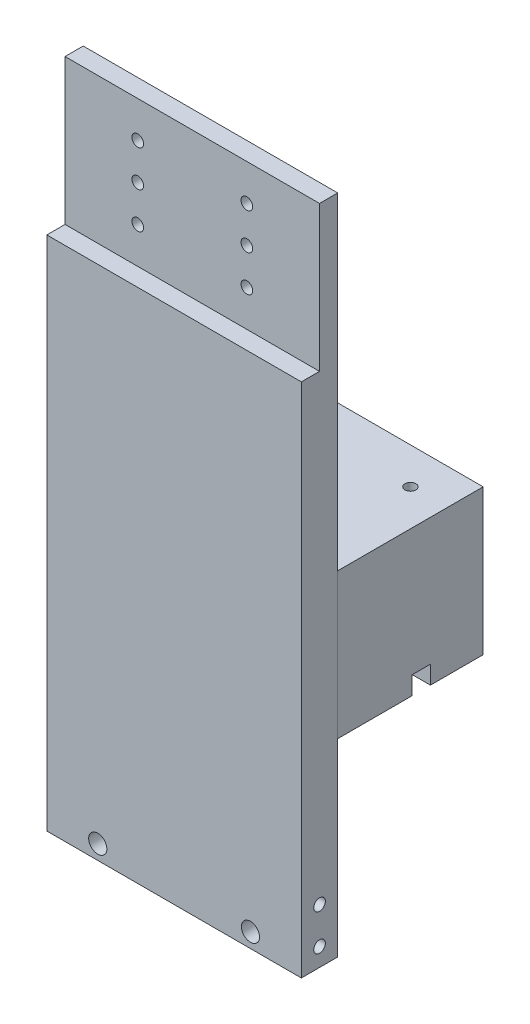
SolidWorks part; units mm, degrees
ref_plane "前视基准面" through (0, 0, 0) normal (0, 0, 1) x (1, 0, 0)
ref_plane "上视基准面" through (0, 0, 0) normal (0, 1, 0) x (1, 0, 0)
ref_plane "右视基准面" through (0, 0, 0) normal (1, 0, 0) x (0, 0, -1)
other "Configuration Table"
sketch "草图1" plane through (0, 0, 0) normal (0, 1, 0) x (1, 0, 0)
  line L1 (-32.1359, 17.2849) -> (37.8641, 17.2849)
  line L2 (-32.1359, 17.2849) -> (-32.1359, -22.7151)
  line L3 (-32.1359, -22.7151) -> (37.8641, -22.7151)
  line L4 (37.8641, 17.2849) -> (37.8641, -22.7151)
  dimension "D1" = 70
  dimension "D2" = 40
extrude "凸台-拉伸1" add sketch "草图1" along normal blind 40
sketch "草图2" plane through (0, 0, 0) normal (0, -1, 0) x (1, 0, 0)
  line L0 (-33.606, 17.7151) -> (40.5423, 17.7151) construction
  line L1 (-32.1359, 22.7151) -> (37.8641, 22.7151) construction
  line L2 (2.8641, 22.7151) -> (2.8641, -17.2849) construction
  line L3 (37.8641, -17.2849) -> (-32.1359, -17.2849) construction
  line L5 (-41.0082, -7.2849) -> (62.2571, -7.2849) construction
  circle A0 centre (-22.1359, 17.7151) radius 1.5
  circle A1 centre (27.8641, 17.7151) radius 1.5
  circle A2 centre (-22.1359, -7.2849) radius 1.5
  circle A3 centre (27.8641, -7.2849) radius 1.5
  dimension "D2" = 25
  dimension "D4" = 25
  dimension "D1" = 5
  dimension "D3" = 10
extrude "切除-拉伸1" cut sketch "草图2" against normal through all
sketch "草图4" plane through (0, 0, 0) normal (0, -1, 0) x (1, 0, 0)
  line L0 (-32.1359, 22.7151) -> (-32.1359, 32.7151)
  line L1 (-32.1359, 32.7151) -> (37.8641, 32.7151)
  line L2 (37.8641, 32.7151) -> (37.8641, 22.7151)
  line L3 (37.8641, 22.7151) -> (-32.1359, 22.7151)
  dimension "D1" = 10
extrude "凸台-拉伸2" add sketch "草图4" along normal blind 52 and the other way blind 236 separate body contours L3 L0 L1 L2
sketch "草图5" plane through (0, 0, 32.7151) normal (0, 0, 1) x (1, 0, 0)
  line L0 (-38.373, -48) -> (39.7493, -48) construction
  line L1 (-32.1359, -52) -> (37.8641, -52) construction
  line L2 (2.8641, 0) -> (2.8641, -52) construction
  line L3 (-32.1359, 0) -> (37.8641, 0) construction
  circle A0 centre (-18.1359, -48) radius 2.5
  circle A1 centre (23.8641, -48) radius 2.5
  dimension "D2" = 21
  dimension "D1" = 4
extrude "切除-拉伸2" cut sketch "草图5" against normal blind 10
sketch "草图6" plane through (0, 0, 32.7151) normal (0, 0, 1) x (1, 0, 0)
  line L0 (-39.8379, 212) -> (51.2489, 212) construction
  line L1 (-32.1359, 236) -> (37.8641, 236) construction
  line L2 (2.8641, 236) -> (2.8641, 203.179) construction
  circle A0 centre (-18.1359, 212) radius 3
  circle A1 centre (23.8641, 212) radius 3
  dimension "D2" = 21
  dimension "D1" = 24
extrude "切除-拉伸3" cut sketch "草图6" against normal blind 10
sketch "草图7" plane through (0, 0, 22.7151) normal (0, 0, -1) x (-1, 0, 0)
  line L0 (-37.8641, 236) -> (-37.8641, 246)
  line L1 (-37.8641, 246) -> (32.1359, 246)
  line L2 (32.1359, 246) -> (32.1359, 236)
  line L3 (32.1359, 236) -> (-37.8641, 236)
  dimension "D1" = 10
extrude "凸台-拉伸3" add sketch "草图7" against normal blind 50
sketch "草图8" plane through (0, 236, 0) normal (0, -1, 0) x (1, 0, 0)
  line L0 (-32.1359, 72.7151) -> (37.8641, 32.7151) construction
  line L1 (37.8641, 72.7151) -> (-32.1359, 32.7151) construction
  circle A0 centre (2.8641, 52.7151) radius 12.5
extrude "切除-拉伸4" cut sketch "草图8" against normal blind 10
sketch "草图12" plane through (0, 246, 0) normal (0, 1, 0) x (1, 0, 0)
  line L0 (2.8641, -52.7151) -> (49.57, -52.7151) construction
  line L1 (2.8641, -52.7151) -> (-42.4096, -52.7151) construction
  line L2 (2.8641, -22.7151) -> (2.8641, -78.6614) construction
  line L3 (-32.1359, -22.7151) -> (37.8641, -22.7151) construction
  line L4 (-14.6359, -35.2151) -> (-14.6359, -70.2151) construction
  line L5 (-16.6359, -33.2151) -> (22.3641, -33.2151)
  line L6 (-16.6359, -33.2151) -> (-16.6359, -72.2151)
  line L7 (-16.6359, -72.2151) -> (22.3641, -72.2151)
  line L8 (22.3641, -33.2151) -> (22.3641, -72.2151)
  line L9 (-14.6359, -70.2151) -> (20.3641, -70.2151) construction
  line L10 (20.3641, -35.2151) -> (20.3641, -70.2151) construction
  line L11 (-14.6359, -35.2151) -> (20.3641, -35.2151) construction
  dimension "D1" = 39
  dimension "D2" = 39
  dimension "D3" = 19.5
  dimension "D5" = 19.5
  dimension "D4" = 2
extrude "拉伸-薄壁2" add sketch "草图12" along normal blind 15 thin
sketch "草图14" plane through (0, 261, 0) normal (0, 1, 0) x (1, 0, 0)
  line L0 (-16.6359, -52.7151) -> (22.3641, -52.7151) construction
  line L1 (-16.6359, -33.2151) -> (-16.6359, -72.2151) construction
  line L2 (22.3641, -72.2151) -> (22.3641, -33.2151) construction
  line L3 (2.8641, -33.2151) -> (2.8641, -72.2151) construction
  line L4 (22.3641, -33.2151) -> (-16.6359, -33.2151) construction
  line L5 (-16.6359, -72.2151) -> (22.3641, -72.2151) construction
  circle A0 centre (-12.6359, -37.2151) radius 2
  circle A1 centre (18.3641, -37.2151) radius 2
  circle A2 centre (-12.6359, -68.2151) radius 2
  circle A3 centre (18.3641, -68.2151) radius 2
  dimension "D1" = 15.5
  dimension "D2" = 15.5
extrude "切除-拉伸5" cut sketch "草图14" against normal blind 25
sketch "草图15" plane through (0, 0, 0) normal (0, -1, 0) x (1, 0, 0)
  line L0 (-32.1359, -0.2849) -> (37.8641, -0.2849) construction
  line L1 (-32.1359, -17.2849) -> (-32.1359, 22.7151) construction
  line L2 (37.8641, 22.7151) -> (37.8641, -17.2849) construction
  line L3 (-32.1359, 2.2151) -> (37.8641, 2.2151)
  line L4 (37.8641, 2.2151) -> (37.8641, -2.7849)
  line L5 (37.8641, -2.7849) -> (-32.1359, -2.7849)
  line L6 (-32.1359, -2.7849) -> (-32.1359, 2.2151)
  circle A0 centre (-22.1359, -7.2849) radius 1.5 construction
  dimension "D1" = 7
  dimension "D2" = 5
  dimension "D3" = 2.5
extrude "切除-拉伸6" cut sketch "草图15" against normal blind 5
sketch "草图16" plane through (-32.1359, 0, 0) normal (-1, 0, 0) x (0, 0, 1)
  line L0 (22.7151, 246) -> (72.7151, 246)
  line L1 (72.7151, 246) -> (72.7151, 236)
  line L2 (72.7151, 236) -> (22.7151, 236)
  line L3 (22.7151, 246) -> (22.7151, -52) construction
  line L4 (22.7151, 236) -> (22.7151, 246)
extrude "凸台-拉伸5" add sketch "草图16" along normal blind 10
ref_plane "基准面3" through (0, 97, 0) normal (0, 1, 0) x (1, 0, 0)
mirror "镜向1" about plane through (0, 97, 0) normal (0, 1, 0) of "凸台-拉伸5"
ref_plane "基准面4" through (2.8641, 0, 0) normal (-1, 0, 0) x (0, 0, 1)
mirror "镜向2" about plane through (2.8641, 0, 0) normal (-1, 0, 0) of "镜向1", "凸台-拉伸5"
sketch "草图17" plane through (0, -52, 0) normal (0, -1, 0) x (1, 0, 0)
  line L0 (-32.1359, 52.7151) -> (37.8641, 52.7151) construction
  line L1 (-32.1359, 72.7151) -> (-32.1359, 32.7151) construction
  line L2 (37.8641, 72.7151) -> (37.8641, 32.7151) construction
  line L3 (2.8641, 72.7151) -> (2.8641, 32.7151) construction
  line L4 (47.8641, 72.7151) -> (-42.1359, 72.7151) construction
  line L5 (-32.1359, 32.7151) -> (37.8641, 32.7151) construction
  circle A0 centre (-37.1359, 52.7151) radius 2.5
  circle A1 centre (42.8641, 52.7151) radius 2.5
  dimension "D1" = 5
extrude "切除-拉伸7" cut sketch "草图17" against normal through all
sketch "草图18" plane through (0, -52, 0) normal (0, -1, 0) x (1, 0, 0)
  circle A0 centre (-37.1359, 52.7151) radius 2.5
  circle A1 centre (42.8641, 52.7151) radius 2.5
extrude "凸台-拉伸6" add sketch "草图18" against normal blind 5
sketch "草图21" plane through (0, 0, 22.7151) normal (0, 0, -1) x (-1, 0, 0)
  line L1 (-37.8641, 236) -> (-37.8641, -42) construction
  line L2 (-37.8641, -32) -> (-37.8641, -42)
  line L3 (-37.8641, -42) -> (-47.8641, -42)
  line L4 (-37.8641, -32) -> (-47.8641, -32)
  line L5 (-47.8641, -32) -> (-47.8641, -42)
  dimension "D1" = 10
extrude "凸台-拉伸8" add sketch "草图21" against normal up to surface (10 mm away) up to face at (-15.1359, 212, 32.7151)
mirror "镜向3" about plane through (2.8641, 0, 0) normal (-1, 0, 0) of "凸台-拉伸8"
sketch "草图22" plane through (47.8641, 0, 0) normal (1, 0, 0) x (0, 0, -1)
  line L0 (-32.7151, -32) -> (-42.7151, -42)
  line L1 (-32.7151, -42) -> (-72.7151, -42) construction
  line L2 (-42.7151, -42) -> (-32.7151, -42)
  line L3 (-32.7151, -42) -> (-32.7151, -32)
  dimension "D1" = 10
extrude "凸台-拉伸9" add sketch "草图22" against normal up to surface (10 mm away) up to face at (37.8641, 102, 27.7151)
sketch "草图23" plane through (-42.1359, 0, 0) normal (-1, 0, 0) x (0, 0, 1)
  line L0 (32.7151, -32) -> (42.7151, -42)
  line L1 (42.7151, -42) -> (32.7151, -42)
  line L2 (32.7151, -52) -> (32.7151, -32) construction
  line L3 (32.7151, -42) -> (32.7151, -32)
extrude "凸台-拉伸10" add sketch "草图23" against normal up to surface (10 mm away) contours L3 L0 L1 up to face at (-32.1359, -47, 52.7151)
sketch "草图25" plane through (-32.1359, 0, 0) normal (-1, 0, 0) x (0, 0, 1)
  line L0 (22.7151, 130) -> (27.7151, 130)
  line L1 (22.7151, 236) -> (22.7151, -32) construction
  line L2 (27.7151, 130) -> (27.7151, 90)
  line L3 (27.7151, 90) -> (32.7151, 90)
  line L4 (32.7151, 236) -> (32.7151, -32) construction
  dimension "D1" = 5
  dimension "D2" = 40
sketch "草图26" plane through (0, 0, 22.7151) normal (0, 0, -1) x (-1, 0, 0)
  line L0 (-43.6159, 100) -> (42.466, 100) construction
  line L1 (-37.8641, 40) -> (32.1359, 40) construction
  line L2 (-48.5792, 110) -> (59.7213, 110) construction
  line L3 (-53.3982, 120) -> (66.4425, 120) construction
  line L4 (-37.8641, 236) -> (-37.8641, -32) construction
  line L5 (32.1359, 130) -> (32.1359, 90) construction
  circle A0 centre (-17.8641, 100) radius 1.6
  circle A1 centre (-17.8641, 110) radius 1.6
  circle A2 centre (-17.8641, 120) radius 1.6
  circle A3 centre (12.1359, 120) radius 1.6
  circle A4 centre (12.1359, 110) radius 1.6
  circle A5 centre (12.1359, 100) radius 1.6
  dimension "D4" = 20
  dimension "D5" = 20
  dimension "D1" = 60
  dimension "D2" = 70
  dimension "D3" = 80
extrude "切除-拉伸8" cut sketch "草图26" against normal blind 10
split "分割1" trim tools "草图25" bodies to split 131 resulting bodies 132 133
other "保存实体1"
delete or keep bodies "实体-删除/保留 1" type delete bodies bodies 134
sketch "草图27" plane through (-42.1359, 0, 0) normal (-1, 0, 0) x (0, 0, 1)
  line L0 (19.3803, -37) -> (42.3867, -37) construction
  line L1 (27.7151, -29.2109) -> (27.7151, -55.3496) construction
  line L2 (18.0924, -47) -> (45.3478, -47) construction
  line L3 (32.7151, -32) -> (22.7151, -32) construction
  line L4 (72.7151, -52) -> (22.7151, -52) construction
  line L5 (22.7151, -52) -> (22.7151, -32) construction
  circle A0 centre (27.7151, -37) radius 1.6
  circle A1 centre (27.7151, -47) radius 1.6
  point P16 (0, 0)
  point P17 (27.7151, -47)
  dimension "D1" = 5
  dimension "D2" = 5
  dimension "D3" = 5
extrude "切除-拉伸9" cut sketch "草图27" against normal through all
sketch "草图28" plane through (0, 0, 22.7151) normal (0, 0, -1) x (-1, 0, 0)
  line L0 (-37.8641, -32) -> (-37.8641, -52)
  line L1 (-47.8641, -52) -> (42.1359, -52) construction
  line L2 (32.1359, -32) -> (32.1359, -52)
split "分割2" trim tools "草图28" bodies to split 135 resulting bodies 136 137 138
other "保存实体2"
delete or keep bodies "实体-删除/保留 2" type delete bodies bodies 139 140
